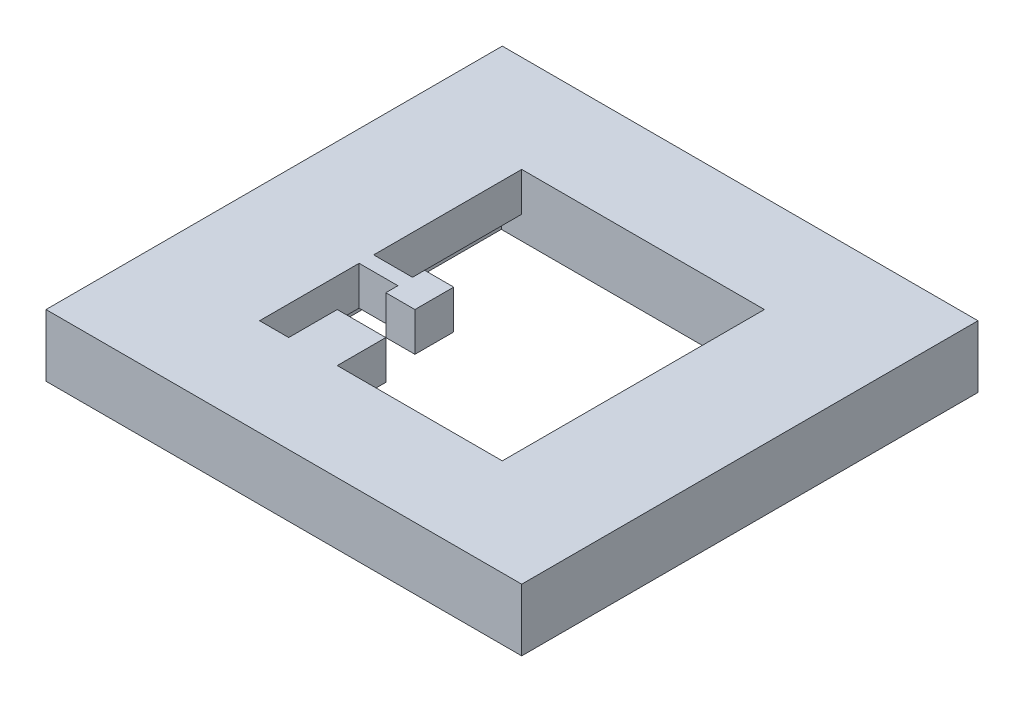
SolidWorks part; units mm, degrees
ref_plane "Front Plane" through (0, 0, 0) normal (0, 0, 1) x (1, 0, 0)
ref_plane "Top Plane" through (0, 0, 0) normal (0, 1, 0) x (1, 0, 0)
ref_plane "Right Plane" through (0, 0, 0) normal (1, 0, 0) x (0, 0, -1)
sketch "Sketch1" plane through (0, 0, 0) normal (0, 1, 0) x (1, 0, 0)
  line L0 (-24.5, -23.5) -> (-24.5, 23.5)
  line L1 (-12.5, -13.5) -> (-9.5, -13.5)
  line L2 (-4.5, -13.5) -> (12.5, -13.5)
  line L3 (-12.5, 13.5) -> (12.5, 13.5)
  line L5 (-14.5, -13.5) -> (14.5, 13.5) construction
  line L6 (-14.5, 13.5) -> (14.5, -13.5) construction
  line L8 (-9.5, -13.5) -> (-9.5, -8.5)
  line L9 (-9.5, -8.5) -> (-4.5, -8.5)
  line L10 (-4.5, -13.5) -> (-4.5, -8.5)
  line L11 (-8.5, -0.5) -> (-5.5, -0.5)
  line L12 (-8.5, -0.5) -> (-8.5, -1.75)
  line L13 (-8.5, -4.5) -> (-5.5, -4.5)
  line L14 (-5.5, -0.5) -> (-5.5, -4.5)
  line L15 (-8.5, -0.5) -> (-5.5, -4.5) construction
  line L16 (-8.5, -4.5) -> (-5.5, -0.5) construction
  line L17 (-24.5, 23.5) -> (24.5, 23.5)
  line L18 (24.5, -23.5) -> (24.5, 23.5)
  line L19 (-24.5, -23.5) -> (24.5, -23.5)
  line L20 (-12.5, -3.25) -> (-12.5, -13.5)
  line L22 (-14.5, -13.5) -> (14.5, -13.5) construction
  line L23 (-14.5, 13.5) -> (14.5, 13.5) construction
  line L24 (-12.5, 13.5) -> (-12.5, -1.75)
  line L28 (12.5, 13.5) -> (12.5, -13.5)
  line L31 (-8.5, -1.75) -> (-12.5, -1.75)
  line L32 (-1.5, -3.25) -> (-12.5, -1.75) construction
  line L33 (-12.5, -3.25) -> (-1.5, -1.75) construction
  line L34 (-8.5, -3.25) -> (-8.5, -4.5)
  line L35 (-8.5, -3.25) -> (-12.5, -3.25)
  line L36 (-14.5, -13.5) -> (-14.5, 13.5) construction
  line L37 (14.5, -13.5) -> (14.5, 13.5) construction
  point P0 (0, 0)
  point P10 (-7, -2.5)
  point P24 (-7, -2.5)
  dimension "D1" = 29
  dimension "D2" = 27
  dimension "D3" = 5
  dimension "D4" = 5
  dimension "D6" = 4
  dimension "D7" = 3
  dimension "D8" = 1
  dimension "D9" = 4
  dimension "D13" = 1.5
  dimension "D10" = 10
extrude "Boss-Extrude1" add sketch "Sketch1" along normal blind 4
sketch "Sketch2" plane through (0, 0, 0) normal (0, -1, 0) x (1, 0, 0)
  line L0 (-12.5, 3.25) -> (-12.5, 13.5) construction
  line L1 (14.6, -13.5) -> (-14.6, -13.5)
  line L2 (14.6, -13.5) -> (14.6, 13.5)
  line L3 (14.6, 13.5) -> (-14.6, 13.5)
  line L4 (24.5, 23.5) -> (-24.5, 23.5)
  line L5 (-24.5, 23.5) -> (-24.5, -23.5)
  line L6 (-24.5, -23.5) -> (24.5, -23.5)
  line L7 (24.5, -23.5) -> (24.5, 23.5)
  line L8 (24.5, 23.5) -> (-24.5, 23.5)
  line L9 (-24.5, 23.5) -> (-24.5, -23.5)
  line L10 (-24.5, -23.5) -> (24.5, -23.5)
  line L11 (24.5, -23.5) -> (24.5, 23.5)
  line L12 (-14.6, -13.5) -> (-14.6, 13.5)
  line L13 (12.5, 13.5) -> (12.5, -13.5) construction
  dimension "D2" = 2.1
  dimension "D3" = 2.1
  dimension "D1" = 0
extrude "Boss-Extrude2" add sketch "Sketch2" along normal blind 2.4
